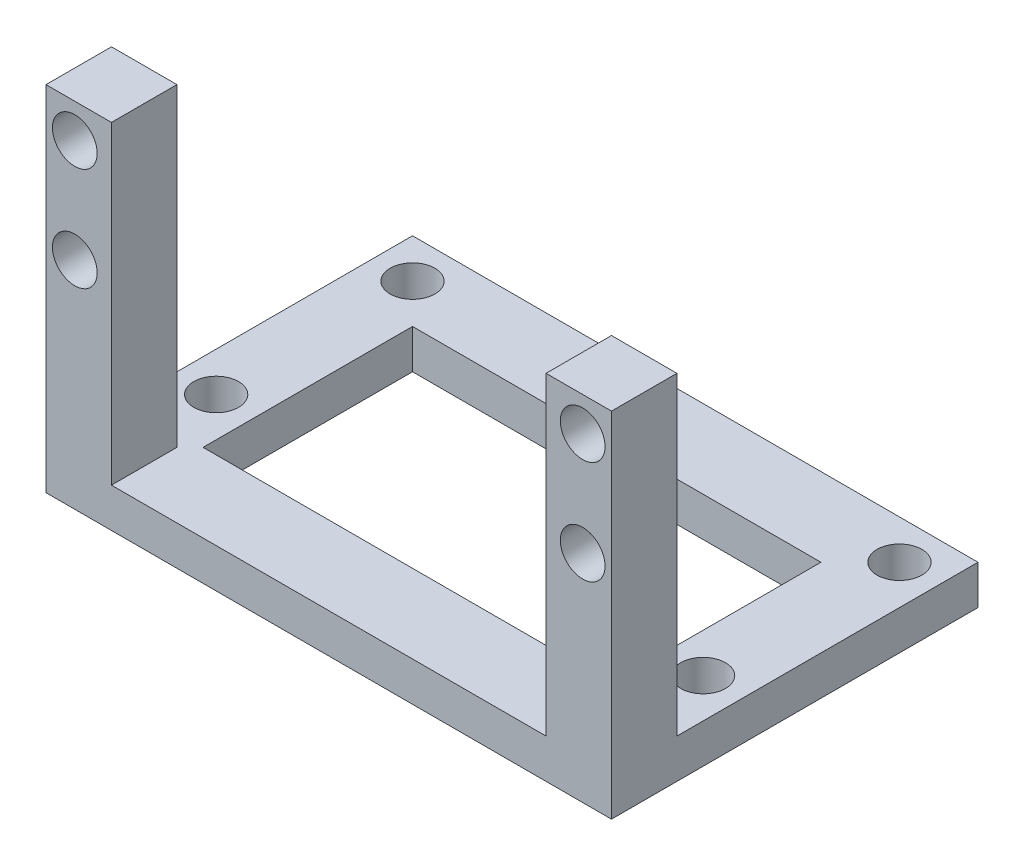
SolidWorks part; units mm, degrees
ref_plane "Front Plane" through (0, 0, 0) normal (0, 0, 1) x (1, 0, 0)
ref_plane "Top Plane" through (0, 0, 0) normal (0, 1, 0) x (1, 0, 0)
ref_plane "Right Plane" through (0, 0, 0) normal (1, 0, 0) x (0, 0, -1)
sketch "Sketch1" plane through (0, 0, 0) normal (0, 1, 0) x (1, 0, 0)
  line L1 (-24.6256, 2.89) -> (30.2384, 2.89)
  line L2 (-24.6256, 2.89) -> (-24.6256, -32.67)
  line L3 (-24.6256, -32.67) -> (30.2384, -32.67)
  line L4 (30.2384, 2.89) -> (30.2384, -32.67)
  dimension "D1" = 54.864
  dimension "D2" = 35.56
extrude "Boss-Extrude1" add sketch "Sketch1" along normal blind 3.81
sketch "Sketch2" plane through (0, 3.81, 0) normal (0, 1, 0) x (1, 0, 0)
  line L0 (30.2384, 2.89) -> (-24.6256, 2.89) construction
  line L1 (-24.6256, 2.89) -> (-24.6256, -32.67) construction
  line L2 (-24.6256, -32.67) -> (30.2384, -32.67) construction
  line L3 (30.2384, -32.67) -> (30.2384, 2.89) construction
  line L5 (-17.0056, -4.73) -> (22.6184, -4.73)
  line L6 (-17.0056, -4.73) -> (-17.0056, -25.05)
  line L7 (-17.0056, -25.05) -> (22.6184, -25.05)
  line L8 (22.6184, -4.73) -> (22.6184, -25.05)
  circle A0 centre (-20.8156, -0.92) radius 2.1717
  circle A1 centre (-20.8156, -19.97) radius 2.1717
  circle A2 centre (26.4284, -19.97) radius 2.1717
  circle A3 centre (26.4284, -0.92) radius 2.1717
  dimension "D1" = 3.81
  dimension "D3" = 3.81
  dimension "D5" = 12.7
  dimension "D7" = 3.81
  dimension "D2" = 3.81
  dimension "D4" = 12.7
  dimension "D6" = 3.81
  dimension "D8" = 3.81
  dimension "D9" = 7.62
  dimension "D10" = 7.62
  dimension "D11" = 7.62
  dimension "D12" = 7.62
extrude "Cut-Extrude2" cut sketch "Sketch2" against normal blind 3.81
sketch "Sketch3" plane through (0, 3.81, 0) normal (0, 1, 0) x (1, 0, 0)
  line L0 (-24.6256, 2.89) -> (-24.6256, -32.67) construction
  line L1 (-24.6256, -26.3171) -> (-18.2756, -26.3171)
  line L2 (-24.6256, -26.3171) -> (-24.6256, -32.67)
  line L3 (-24.6256, -32.67) -> (-18.2756, -32.67)
  line L4 (-18.2756, -26.3171) -> (-18.2756, -32.67)
  line L5 (-24.6256, -32.67) -> (30.2384, -32.67) construction
  line L6 (30.2384, -32.67) -> (30.2384, 2.89) construction
  line L7 (30.2384, -26.32) -> (23.8884, -26.32)
  line L8 (30.2384, -26.32) -> (30.2384, -32.67)
  line L9 (30.2384, -32.67) -> (23.8884, -32.67)
  line L10 (23.8884, -26.32) -> (23.8884, -32.67)
  dimension "D1" = 6.35
  dimension "D2" = 6.3528
  dimension "D3" = 6.35
  dimension "D4" = 6.35
extrude "Boss-Extrude2" add sketch "Sketch3" along normal blind 30.48
sketch "Sketch4" plane through (0, 0, 32.67) normal (0, 0, 1) x (1, 0, 0)
  line L1 (-24.6256, 34.29) -> (-18.2756, 34.29) construction
  line L3 (-24.6256, 34.29) -> (-24.6256, 0) construction
  line L4 (23.8884, 34.29) -> (30.2384, 34.29) construction
  line L5 (30.2384, 34.29) -> (30.2384, 0) construction
  circle A0 centre (-21.8316, 30.988) radius 2.1717
  circle A1 centre (-21.8316, 20.955) radius 2.1717
  circle A2 centre (27.4444, 30.988) radius 2.1717
  circle A3 centre (27.4444, 20.955) radius 2.1717
  dimension "D1" = 4.3434
  dimension "D2" = 3.302
  dimension "D4" = 4.3434
  dimension "D7" = 4.3434
  dimension "D10" = 10.033
  dimension "D11" = 2.794
  dimension "D3" = 2.794
  dimension "D5" = 2.794
  dimension "D6" = 10.033
  dimension "D8" = 3.302
  dimension "D9" = 2.794
extrude "Cut-Extrude3" cut sketch "Sketch4" against normal blind 6.35
